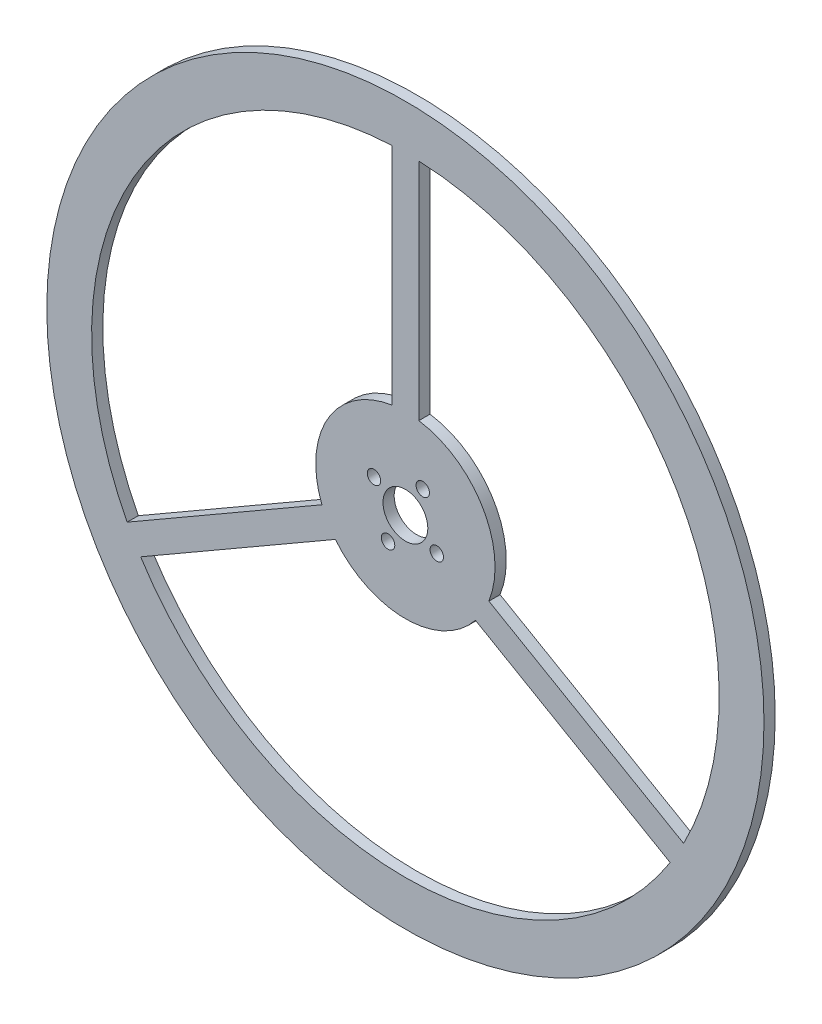
SolidWorks part; units mm, degrees
ref_plane "前视基准面" through (0, 0, 0) normal (0, 0, 1) x (1, 0, 0)
ref_plane "上视基准面" through (0, 0, 0) normal (0, 1, 0) x (1, 0, 0)
ref_plane "右视基准面" through (0, 0, 0) normal (1, 0, 0) x (0, 0, -1)
other "Configuration Table"
sketch "草图1" plane through (0, 0, 0) normal (0, 0, 1) x (1, 0, 0)
  line L0 (-3, 19.7737) -> (-3, 69.9357)
  line L1 (3, 19.7737) -> (3, 69.9357)
  line L2 (0, 0) -> (0, 39.9657) construction
  line L3 (18.6245, -7.2888) -> (62.0661, -32.3698)
  line L4 (15.6245, -12.4849) -> (59.0661, -37.5659)
  line L5 (-15.6245, -12.4849) -> (-59.0661, -37.5659)
  line L6 (-18.6245, -7.2888) -> (-62.0661, -32.3698)
  circle A1 centre (0, 0) radius 80
  arc A2 (-3, 69.9357) -> (-62.0661, -32.3698) centre (0, 0) ccw
  circle A3 centre (0, 0) radius 5
  arc A4 (18.6245, -7.2888) -> (3, 19.7737) centre (0, 0) ccw
  arc A5 (-59.0661, -37.5659) -> (59.0661, -37.5659) centre (0, 0) ccw
  arc A6 (62.0661, -32.3698) -> (3, 69.9357) centre (0, 0) ccw
  arc A7 (-3, 19.7737) -> (-18.6245, -7.2888) centre (0, 0) ccw
  arc A8 (-15.6245, -12.4849) -> (15.6245, -12.4849) centre (0, 0) ccw
  point P22 (0, 0)
  dimension "D1" = 160
  dimension "D2" = 140
  dimension "D4" = 10
  dimension "D3" = 40
  dimension "D5" = 6
  dimension "D6" = 3
extrude "凸台-拉伸1" add sketch "草图1" along normal blind 2.5
sketch "草图2" plane through (0, 0, 0) normal (0, 0, -1) x (-1, 0, 0)
  circle A0 centre (-7.0009, -3.8714) radius 1.5
  circle A1 centre (-3.8714, 7.0009) radius 1.5
  circle A2 centre (7.0009, 3.8714) radius 1.5
  circle A3 centre (3.8714, -7.0009) radius 1.5
  point P12 (0, 0)
  dimension "D1" = 4
extrude "切除-拉伸1" cut sketch "草图2" against normal through all
